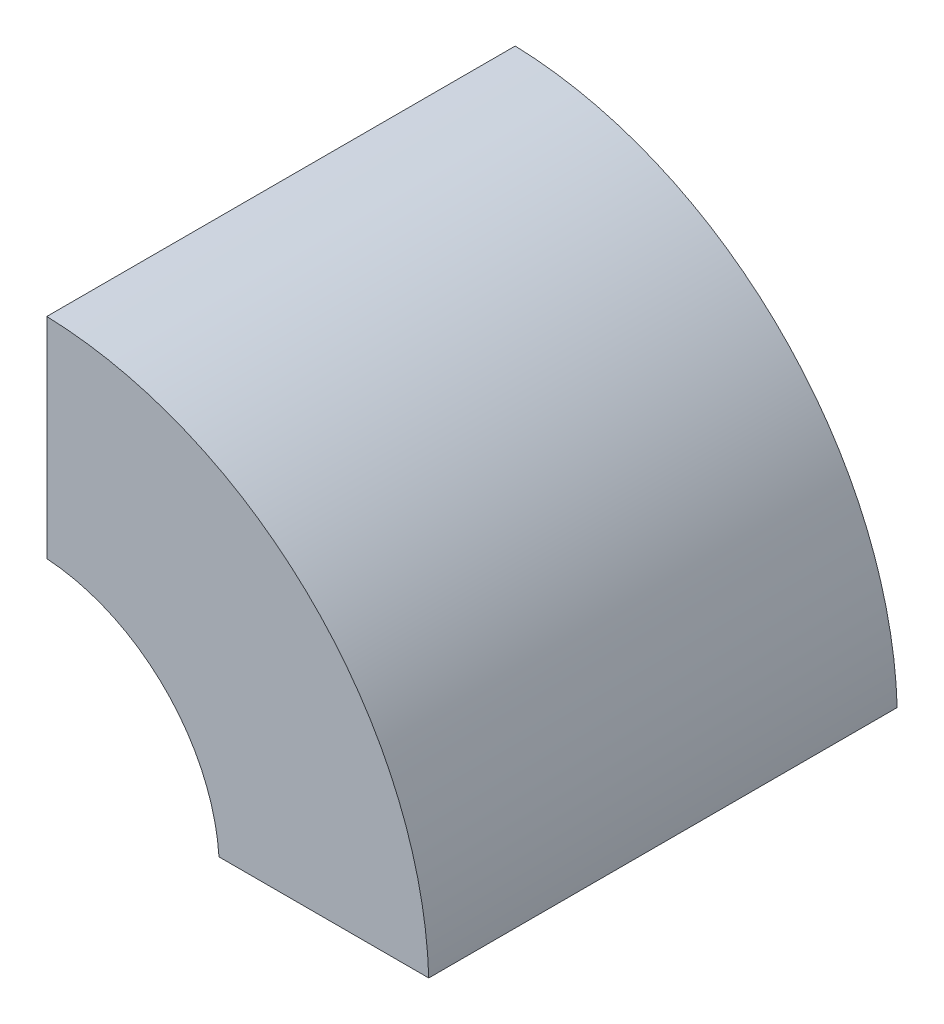
SolidWorks part; units mm, degrees
ref_plane "Front Plane" through (0, 0, 0) normal (0, 0, 1) x (1, 0, 0)
ref_plane "Top Plane" through (0, 0, 0) normal (0, 1, 0) x (1, 0, 0)
ref_plane "Right Plane" through (0, 0, 0) normal (1, 0, 0) x (0, 0, -1)
sketch "Sketch1" plane through (0, 0, 0) normal (0, 0, 1) x (1, 0, 0)
  line L0 (0.5, 15.9922) -> (0.5, 7.4833)
  line L1 (7.4833, 0.5) -> (15.9922, 0.5)
  arc A0 (7.4833, 0.5) -> (0.5, 7.4833) centre (0, 0) ccw
  arc A1 (15.9922, 0.5) -> (0.5, 15.9922) centre (0, 0) ccw
  point P1 (0, 0)
  dimension "D1" = 16
extrude "Boss-Extrude1" add sketch "Sketch1" against normal blind 19
